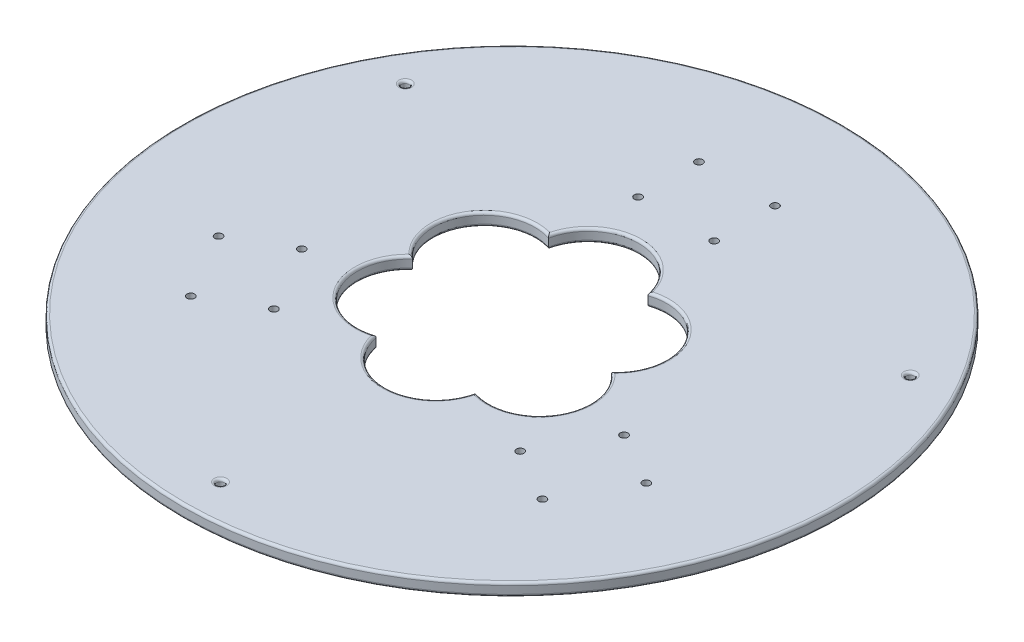
SolidWorks part; units mm, degrees
ref_plane "前视基准面" through (0, 0, 0) normal (0, 0, 1) x (1, 0, 0)
ref_plane "上视基准面" through (0, 0, 0) normal (0, 1, 0) x (1, 0, 0)
ref_plane "右视基准面" through (0, 0, 0) normal (1, 0, 0) x (0, 0, -1)
sketch "Sketch1" plane through (0, 0, 0) normal (0, 1, 0) x (1, 0, 0)
  line L0 (0, 0) -> (-118.8255, 68.6039) construction
  line L1 (0, 152.1369) -> (0, -143.8386) construction
  line L2 (0, 0) -> (140.1229, 80.9) construction
  line L3 (0, 0) -> (245.7953, -141.91) construction
  line L4 (0, -30) -> (0, 30) construction
  line L6 (-20, -30) -> (-20, 30)
  line L7 (20, -30) -> (20, 30)
  line L8 (-25.9808, 15) -> (25.9808, -15) construction
  line L9 (-15.9808, 32.3205) -> (35.9808, 2.3205)
  line L10 (-35.9808, -2.3205) -> (15.9808, -32.3205)
  line L11 (25.9808, 15) -> (-25.9808, -15) construction
  line L12 (35.9808, -2.3205) -> (-15.9808, -32.3205)
  line L13 (15.9808, 32.3205) -> (-35.9808, 2.3205)
  circle A0 centre (0, 0) radius 130
  circle A1 centre (-15, 88.7412) radius 1.5
  circle A2 centre (15, 88.7412) radius 1.5
  circle A3 centre (-15, 64.7412) radius 1.5
  circle A4 centre (15, 64.7412) radius 1.5
  circle A5 centre (84.3521, -31.3802) radius 1.5
  circle A6 centre (69.3521, -57.361) radius 1.5
  circle A7 centre (63.5675, -19.3802) radius 1.5
  circle A8 centre (48.5675, -45.361) radius 1.5
  circle A9 centre (-69.3521, -57.361) radius 1.5
  circle A10 centre (-84.3521, -31.3802) radius 1.5
  circle A11 centre (-48.5675, -45.361) radius 1.5
  circle A12 centre (-63.5675, -19.3802) radius 1.5
  arc A13 (-20, -30) -> (20, -30) centre (0, -30) ccw
  arc A14 (20, 30) -> (-20, 30) centre (0, 30) ccw
  circle A16 centre (-99.5929, 57.5) radius 1.5
  circle A17 centre (99.5929, 57.5) radius 1.5
  circle A18 centre (0, -115) radius 1.5
  arc A19 (-15.9808, 32.3205) -> (-35.9808, -2.3205) centre (-25.9808, 15) ccw
  arc A20 (15.9808, -32.3205) -> (35.9808, 2.3205) centre (25.9808, -15) ccw
  arc A21 (35.9808, -2.3205) -> (15.9808, 32.3205) centre (25.9808, 15) ccw
  arc A22 (-35.9808, 2.3205) -> (-15.9808, -32.3205) centre (-25.9808, -15) ccw
  point P34 (0, 0)
  point P39 (0, 0)
  point P51 (0, 0)
  point P54 (0, 0)
  point P61 (0, 0)
  point P66 (0, 0)
  dimension "D1" = 260
  dimension "D4" = 3
  dimension "D6" = 90
  dimension "D11" = 15
  dimension "D12" = 20
  dimension "D14" = 3
  dimension "D2" = 60
  dimension "D3" = 60
  dimension "D5" = 15
  dimension "D8" = 24
  dimension "D10" = 90
  dimension "D13" = 60
  dimension "D15" = 115
  dimension "D17" = 115
  dimension "D18" = 115
  dimension "D7" = 2
  dimension "D9" = 3
  dimension "D16" = 3
  dimension "D19" = 3
extrude "Boss-Extrude1" add sketch "Sketch1" along normal blind 5 contours A0 A22 A19 A14 A21 A20 A13 A18 A17 A16 A10 A9 A6 A5 A2 A1 A3 A4 A7 A8 A11 A12
fillet "Fillet1" radius 1 20 edges at (0, 0, 130) (0, 5, 130) (-99.5929, 5, -56) (99.5929, 5, -56) (0, 5, 116.5) (0, 5, 50) (43.3013, 5, 25) (43.3013, 5, -25) (0, 5, -50) (-43.3013, 5, 25) (-43.3013, 5, -25) (-99.5929, 0, -56) (99.5929, 0, -56) (0, 0, 116.5) (0, 0, -50) (43.3013, 0, -25) (43.3013, 0, 25) (0, 0, 50) (-43.3013, 0, 25) (-43.3013, 0, -25)
